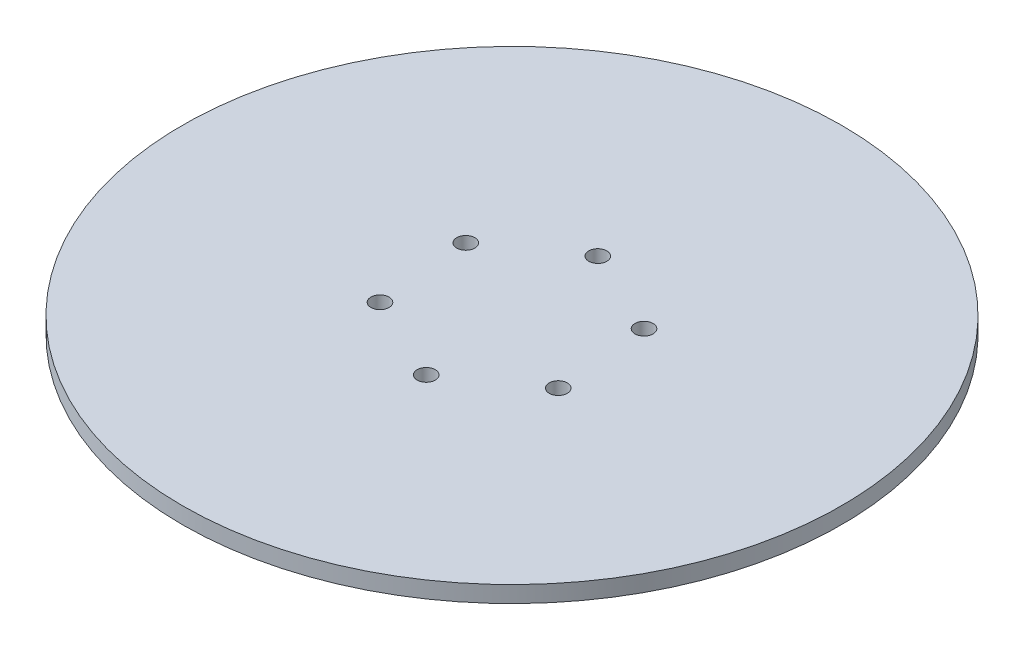
SolidWorks part; units mm, degrees
ref_plane "前视基准面" through (0, 0, 0) normal (0, 0, 1) x (1, 0, 0)
ref_plane "上视基准面" through (0, 0, 0) normal (0, 1, 0) x (1, 0, 0)
ref_plane "右视基准面" through (0, 0, 0) normal (1, 0, 0) x (0, 0, -1)
other "Configuration Table"
sketch "草图2" plane through (0, 0, 0) normal (0, 1, 0) x (1, 0, 0)
  circle A0 centre (0, 0) radius 60
  dimension "D1" = 120
extrude "凸台-拉伸1" add sketch "草图2" along normal blind 3
sketch "草图3" plane through (0, 0, 0) normal (0, -1, 0) x (1, 0, 0)
  arc A0 (17.0053, 6.2903) -> (14.308, 8.1916) centre (15.6567, 7.241) ccw construction
  arc A1 (14.308, 8.1916) -> (17.0053, 6.2903) centre (15.6567, 7.241) ccw construction
  arc A2 (15.4478, -10.8892) -> (12.7506, -8.9879) centre (14.0992, -9.9386) ccw construction
  arc A3 (12.7506, -8.9879) -> (15.4478, -10.8892) centre (14.0992, -9.9386) ccw construction
  arc A4 (-0.2088, -18.1302) -> (-2.9061, -16.2289) centre (-1.5575, -17.1795) ccw construction
  arc A5 (-2.9061, -16.2289) -> (-0.2088, -18.1302) centre (-1.5575, -17.1795) ccw construction
  arc A6 (-14.308, -8.1916) -> (-17.0053, -6.2903) centre (-15.6567, -7.241) ccw construction
  arc A7 (-17.0053, -6.2903) -> (-14.308, -8.1916) centre (-15.6567, -7.241) ccw construction
  arc A8 (-12.7506, 8.9879) -> (-15.4478, 10.8892) centre (-14.0992, 9.9386) ccw construction
  arc A9 (-15.4478, 10.8892) -> (-12.7506, 8.9879) centre (-14.0992, 9.9386) ccw construction
  arc A10 (2.9061, 16.2289) -> (0.2088, 18.1302) centre (1.5575, 17.1795) ccw construction
  arc A11 (0.2088, 18.1302) -> (2.9061, 16.2289) centre (1.5575, 17.1795) ccw construction
  arc A12 (17.0053, 6.2903) -> (14.308, 8.1916) centre (15.6567, 7.241) ccw
  arc A13 (14.308, 8.1916) -> (17.0053, 6.2903) centre (15.6567, 7.241) ccw
  arc A14 (15.4478, -10.8892) -> (12.7506, -8.9879) centre (14.0992, -9.9386) ccw
  arc A15 (12.7506, -8.9879) -> (15.4478, -10.8892) centre (14.0992, -9.9386) ccw
  arc A16 (-0.2088, -18.1302) -> (-2.9061, -16.2289) centre (-1.5575, -17.1795) ccw
  arc A17 (-2.9061, -16.2289) -> (-0.2088, -18.1302) centre (-1.5575, -17.1795) ccw
  arc A18 (-14.308, -8.1916) -> (-17.0053, -6.2903) centre (-15.6567, -7.241) ccw
  arc A19 (-17.0053, -6.2903) -> (-14.308, -8.1916) centre (-15.6567, -7.241) ccw
  arc A20 (-12.7506, 8.9879) -> (-15.4478, 10.8892) centre (-14.0992, 9.9386) ccw
  arc A21 (-15.4478, 10.8892) -> (-12.7506, 8.9879) centre (-14.0992, 9.9386) ccw
  arc A22 (2.9061, 16.2289) -> (0.2088, 18.1302) centre (1.5575, 17.1795) ccw
  arc A23 (0.2088, 18.1302) -> (2.9061, 16.2289) centre (1.5575, 17.1795) ccw
extrude "切除-拉伸1" cut sketch "草图3" against normal blind 10
